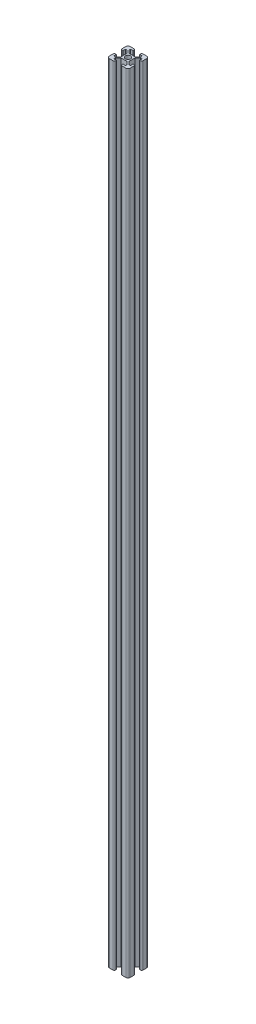
SolidWorks part; units mm, degrees
material "2024 合金"
ref_plane "前视基准面" through (0, 0, 0) normal (0, 0, 1) x (1, 0, 0)
ref_plane "上视基准面" through (0, 0, 0) normal (0, 1, 0) x (1, 0, 0)
ref_plane "右视基准面" through (0, 0, 0) normal (1, 0, 0) x (0, 0, -1)
sketch "草图1" plane through (0, 0, 0) normal (0, 1, 0) x (1, 0, 0)
  line L0 (9.95, -9.95) -> (5.59, -9.95)
  line L1 (-9.95, -9.95) -> (9.95, -9.95)
  line L2 (-9.95, -9.95) -> (-9.95, 9.95)
  line L3 (-9.95, 9.95) -> (9.95, 9.95)
  line L4 (9.95, -9.95) -> (9.95, 9.95)
  line L5 (-9.95, -9.95) -> (9.95, 9.95) construction
  line L6 (-9.95, 9.95) -> (9.95, -9.95) construction
  line L7 (-3.8, 3.8) -> (3.8, 3.8)
  line L8 (-3.8, 3.8) -> (-3.8, -3.8)
  line L9 (-3.8, -3.8) -> (3.8, -3.8)
  line L10 (3.8, 3.8) -> (3.8, -3.8)
  line L11 (-3.8, 3.8) -> (3.8, -3.8) construction
  line L12 (-3.8, -3.8) -> (3.8, 3.8) construction
  line L13 (9.95, 9.95) -> (5.59, 9.95)
  line L14 (9.95, 9.95) -> (9.95, 5.59)
  line L15 (9.95, 5.59) -> (5.59, 5.59)
  line L16 (5.59, 9.95) -> (5.59, 5.59)
  line L17 (9.95, -9.95) -> (9.95, -5.59)
  line L18 (9.95, -5.59) -> (5.59, -5.59)
  line L19 (5.59, -9.95) -> (5.59, -5.59)
  line L20 (-9.95, -9.95) -> (-9.95, -5.59)
  line L21 (-9.95, -9.95) -> (-5.59, -9.95)
  line L22 (-5.59, -9.95) -> (-5.59, -5.59)
  line L23 (-9.95, -5.59) -> (-5.59, -5.59)
  line L24 (-9.95, 9.95) -> (-5.59, 9.95)
  line L25 (-9.95, 9.95) -> (-9.95, 5.59)
  line L26 (-9.95, 5.59) -> (-5.59, 5.59)
  line L27 (-5.59, 9.95) -> (-5.59, 5.59)
  line L28 (-9.95, -9.1015) -> (9.1015, 9.95)
  line L29 (9.95, 9.1015) -> (-9.1015, -9.95)
  line L30 (-9.95, 9.1015) -> (9.1015, -9.95)
  line L31 (9.95, -9.1015) -> (-9.1015, 9.95)
  line L32 (9.95, 9.95) -> (7.95, 9.95)
  line L33 (-9.95, 9.95) -> (-7.95, 9.95)
  line L34 (-9.95, 9.95) -> (-9.95, 3.17)
  line L35 (-9.95, 3.17) -> (-7.95, 3.17)
  line L36 (-7.95, 9.95) -> (-7.95, 3.17)
  line L37 (-9.95, 9.95) -> (-3.17, 9.95)
  line L38 (-9.95, 9.95) -> (-9.95, 7.95)
  line L39 (-9.95, 7.95) -> (-3.17, 7.95)
  line L40 (-3.17, 9.95) -> (-3.17, 7.95)
  line L41 (9.95, 9.95) -> (9.95, 3.17)
  line L42 (9.95, 3.17) -> (7.95, 3.17)
  line L43 (7.95, 9.95) -> (7.95, 3.17)
  line L44 (9.95, 9.95) -> (3.17, 9.95)
  line L45 (9.95, 9.95) -> (9.95, 7.95)
  line L46 (9.95, 7.95) -> (3.17, 7.95)
  line L47 (3.17, 9.95) -> (3.17, 7.95)
  line L48 (9.95, -9.95) -> (9.95, -7.95)
  line L49 (9.95, -9.95) -> (3.17, -9.95)
  line L50 (3.17, -9.95) -> (3.17, -7.95)
  line L51 (9.95, -7.95) -> (3.17, -7.95)
  line L52 (9.95, -9.95) -> (9.95, -3.17)
  line L53 (9.95, -9.95) -> (7.95, -9.95)
  line L54 (7.95, -9.95) -> (7.95, -3.17)
  line L55 (9.95, -3.17) -> (7.95, -3.17)
  line L56 (-9.95, -9.95) -> (-7.95, -9.95)
  line L57 (-9.95, -9.95) -> (-9.95, -3.17)
  line L58 (-9.95, -3.17) -> (-7.95, -3.17)
  line L59 (-7.95, -9.95) -> (-7.95, -3.17)
  line L60 (-9.95, -9.95) -> (-3.17, -9.95)
  line L61 (-9.95, -9.95) -> (-9.95, -7.95)
  line L62 (-9.95, -7.95) -> (-3.17, -7.95)
  line L63 (-3.17, -9.95) -> (-3.17, -7.95)
  circle A0 centre (0, 0) radius 2.5
  point P0 (0, 0)
  point P18 (0, 0)
  point P23 (0, 0)
  point P28 (0, 0)
  point P33 (0, 0)
  point P69 (0, 0)
  dimension "D3" = 5
  dimension "D1" = 19.9
  dimension "D2" = 19.9
  dimension "D4" = 7.6
  dimension "D5" = 7.6
  dimension "D6" = 4.36
  dimension "D8" = 1.2
  dimension "D9" = 1.2
  dimension "D10" = 6.78
  dimension "D11" = 2
  dimension "D12" = 6.78
  dimension "D13" = 2
  dimension "D7" = 4
  dimension "D14" = 4
extrude "凸台-拉伸1" add sketch "草图1" along normal blind 750 contours L40 L3 L27 L39 | L31 L39 L27 L3 L36 | L36 L24 L31 | L30 L39 L36 L31 L3 L25 | L34 L39 L30 | L39 L2 L26 L36 L30 | L36 L39 L31 | L39 L30 L36 | L36 L26 L2 L35 | L39 L31 L27 | L39 L36 L30 L26 L27 L31 | L30 L36 L26 | L7 L31 L27 L26 L30 L8 | L3 L47 L46 L16 | L46 L28 L43 L3 L16 | L13 L43 L28 | L46 L29 L14 L13 L28 L43 | L46 L41 L29 | L4 L46 L29 L43 L15 | L46 L43 L28 | L29 L46 L43 | L15 L43 L42 L4 | L43 L46 L28 L16 L15 L29 | L43 L29 L15 | L28 L46 L16 | L29 L15 L16 L28 L7 L10 | L4 L55 L54 L18 | L54 L31 L51 L4 L18 | L17 L51 L31 | L54 L30 L0 L4 L31 L51 | L54 L1 L30 | L54 L51 L31 | L30 L54 L51 | L49 L54 L30 L51 L19 | L19 L51 L50 L1 | L51 L30 L19 | L51 L54 L31 L18 L19 L30 | L31 L54 L18 | L23 L59 L58 L2 | L57 L62 L28 L59 L23 | L59 L28 L23 | L59 L62 L29 L22 L23 L28 | L29 L62 L22 | L62 L29 L59 L1 L22 | L1 L63 L62 L22 | L62 L59 L29 | L28 L62 L59 | L62 L28 L2 L1 L29 L59 | L62 L20 L28 | L21 L59 L29 | L29 L9 L8 L28 L23 L22 | L18 L31 L10 L9 L30 L19 | A0 L31 L10 L29 | A0 L28 L7 L31 | A0 L30 L8 L28 | A0 L29 L9 L30 | A0 L28 L8 L9 L29 | A0 L30 L9 L10 L31 | A0 L29 L10 L7 L28 | A0 L31 L7 L8 L30
fillet "圆角1" radius 2 4 edges at (9.95, 375, -9.95) (9.95, 375, 9.95) (-9.95, 375, 9.95) (-9.95, 375, -9.95)
fillet "圆角2" radius 1 8 edges at (3.17, 375, -9.95) (-3.17, 375, -9.95) (9.95, 375, 3.17) (9.95, 375, -3.17) (3.17, 375, 9.95) (-3.17, 375, 9.95) (-9.95, 375, -3.17) (-9.95, 375, 3.17)
